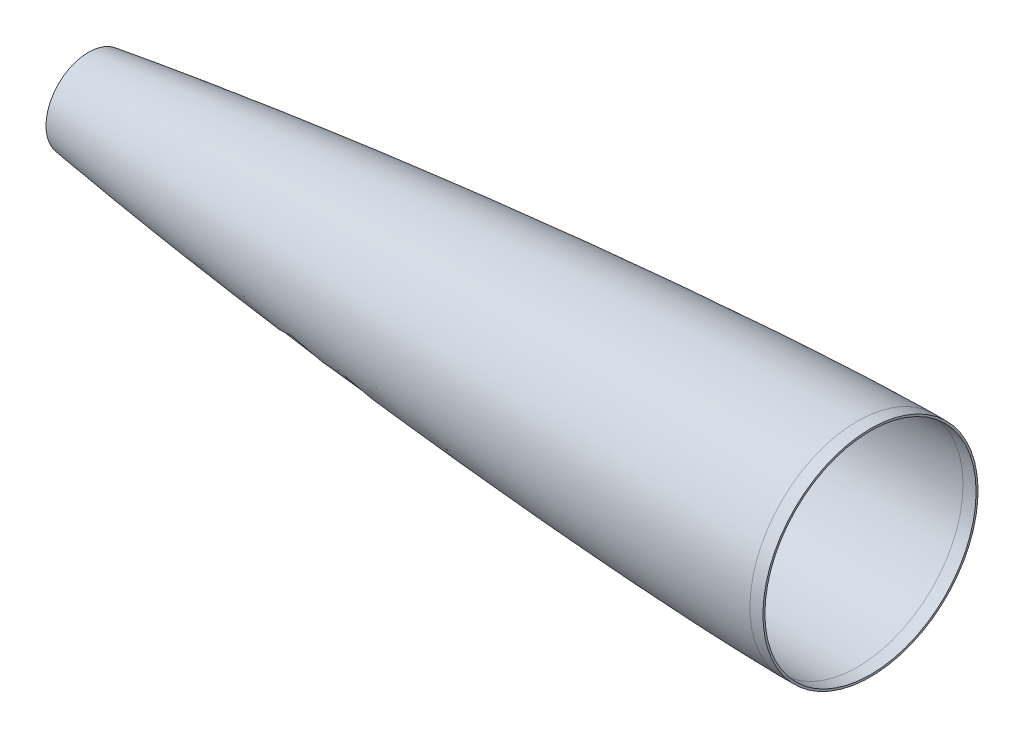
SolidWorks part; units mm, degrees
material "Carbon 4 layer"
ref_plane "Front" through (0, 0, 0) normal (0, 0, 1) x (1, 0, 0)
ref_plane "Top" through (0, 0, 0) normal (0, 1, 0) x (1, 0, 0)
ref_plane "Right" through (0, 0, 0) normal (1, 0, 0) x (0, 0, -1)
sketch "Sketch7" plane through (0, 0, 0) normal (0, 0, 1) x (1, 0, 0)
  line L0 (0, 0) -> (1126.623, 0) construction
  line L1 (762, 82.3169) -> (762, 0)
  line L2 (0, 0) -> (762, 0)
  line L4 (0, 0) -> (0, 4.3134) construction
  line L5 (762, 82.3169) -> (762, 83.8413)
  line L6 (0, 1.923) -> (0, 0)
  line L7 (0, 0) -> (-0.1289, 0.6139)
  spline S0 degree 1 poles (1.2262, -0.9049) (762.0041, 82.3173) knots 0 0 1 1 construction
  spline S1 degree 3 poles (1.2262, -0.9049) (1.2924, -0.8546) (1.418, -0.7697) (1.7793, -0.5514) (2.2706, -0.2924) (2.9029, 0.0097) (3.7722, 0.3946) (4.8926, 0.8497) (6.7216, 1.5355) (9.0513, 2.3331) (12.826, 3.5228) (17.5993, 4.891) (23.3736, 6.4132) (29.1765, 7.8461) (36.943, 9.664) (46.6891, 11.7983) (58.4249, 14.1977) (70.1889, 16.4736) (81.9746, 18.6463) (97.7126, 21.4265) (117.4207, 24.7165) (141.1109, 28.4298) (164.8333, 31.9464) (188.5817, 35.294) (212.3516, 38.4927) (244.0696, 42.5777) (283.7575, 47.3754) (331.4345, 52.7017) (379.1549, 57.6329) (426.9127, 62.1913) (490.6346, 67.7827) (554.4171, 72.6493) (618.2524, 76.7094) (658.1703, 78.8667) (690.1157, 80.3159) (714.0804, 81.2402) (734.0521, 81.8502) (750.034, 82.191) (758.0128, 82.3066) (762.0041, 82.3173) knots 0.000567 0.000567 0.000567 0.000567 0.001055 0.001544 0.00252 0.003496 0.004472 0.006424 0.008376 0.01228 0.016184 0.023992 0.0318 0.039608 0.047416 0.063032 0.078648 0.094264 0.10988 0.125497 0.156729 0.187961 0.219193 0.250426 0.281658 0.31289 0.375355 0.437819 0.500284 0.562748 0.625213 0.750142 0.812606 0.875071 0.906303 0.937535 0.968768 0.984384 1 1 1 1
  spline S2 degree 4 poles (0, 0) (0.0025, 0.0077) (0.0085, 0.0225) (0.0254, 0.0499) (0.0657, 0.1001) (0.1275, 0.1632) (0.2121, 0.2373) (0.3323, 0.3316) (0.4768, 0.4341) (0.6465, 0.5448) (0.8414, 0.663) (1.1269, 0.8263) (1.5727, 1.0629) (2.3354, 1.4323) (3.7109, 2.0298) (6.1546, 2.9698) (10.668, 4.4903) (18.9995, 6.9173) (33.3858, 10.5209) (58.2147, 15.8817) (92.5014, 22.2364) (134.3472, 29.0669) (181.2323, 35.9138) (228.1994, 42.1676) (275.2294, 47.9287) (322.3096, 53.2619) (369.4323, 58.2049) (416.5919, 62.7813) (463.7847, 67.0021) (511.0079, 70.8684) (558.2595, 74.3704) (605.5383, 77.4858) (646.9303, 79.8373) (682.4256, 81.5392) (710.8634, 82.6554) (729.8529, 83.259) (745.3094, 83.6328) (754.8465, 83.7859) (759.6154, 83.8349) (762, 83.8413) knots 0 0 0 0 0 0.000042 0.000084 0.000167 0.000334 0.000501 0.000668 0.000962 0.001257 0.001556 0.001855 0.002675 0.003884 0.005967 0.009662 0.016304 0.028676 0.05114 0.086868 0.148544 0.21022 0.271896 0.333573 0.395249 0.456925 0.518602 0.580278 0.641954 0.70363 0.765307 0.826983 0.888659 0.919497 0.950336 0.975168 0.987584 1 1 1 1 1 construction
  spline S3 degree 4 poles (0, 0) (0.0025, 0.0077) (0.0085, 0.0225) (0.0254, 0.0499) (0.0657, 0.1001) (0.1275, 0.1632) (0.2121, 0.2373) (0.3323, 0.3316) (0.4768, 0.4341) (0.6465, 0.5448) (0.8414, 0.663) (1.1269, 0.8263) (1.5727, 1.0629) (2.3354, 1.4323) (3.7109, 2.0298) (6.1546, 2.9698) (10.668, 4.4903) (18.9995, 6.9173) (33.3858, 10.5209) (58.2147, 15.8817) (92.5014, 22.2364) (134.3472, 29.0669) (181.2323, 35.9138) (228.1994, 42.1676) (275.2294, 47.9287) (322.3096, 53.2619) (369.4323, 58.2049) (416.5919, 62.7813) (463.7847, 67.0021) (511.0079, 70.8684) (558.2595, 74.3704) (605.5383, 77.4858) (646.9303, 79.8373) (682.4256, 81.5392) (710.8634, 82.6554) (729.8529, 83.259) (745.3094, 83.6328) (754.8465, 83.7859) (759.6154, 83.8349) (762, 83.8413) knots 0 0 0 0 0 0.000042 0.000084 0.000167 0.000334 0.000501 0.000668 0.000962 0.001257 0.001556 0.001855 0.002675 0.003884 0.005967 0.009662 0.016304 0.028676 0.05114 0.086868 0.148544 0.21022 0.271896 0.333573 0.395249 0.456925 0.518602 0.580278 0.641954 0.70363 0.765307 0.826983 0.888659 0.919497 0.950336 0.975168 0.987584 1 1 1 1 1
  point P9 (0, 1.923)
  dimension "D1" = 1.524
revolve "Revolve3" add sketch "Sketch7" angle 360 about L2
sketch "Sketch8" plane through (762, 0, 0) normal (1, 0, 0) x (0, 0, -1)
  circle A5 centre (0, 0) radius 82.3172 construction
  circle A6 centre (0, 0) radius 83.8413
  circle A7 centre (0, 0) radius 83.8413
  circle A8 centre (0, 0) radius 82.3172
  dimension "D1" = 0
extrude "Boss-Extrude1" add sketch "Sketch8" along normal blind 10.16
ref_plane "Plane1" through (162.56, 0, 0) normal (1, 0, 0) x (0, 0, -1)
sketch "Sketch9" plane through (162.56, 0, 0) normal (1, 0, 0) x (0, 0, -1)
  circle A0 centre (0, 0) radius 78.3589
extrude "Cut-Extrude1" cut sketch "Sketch9" against normal blind 187.96
